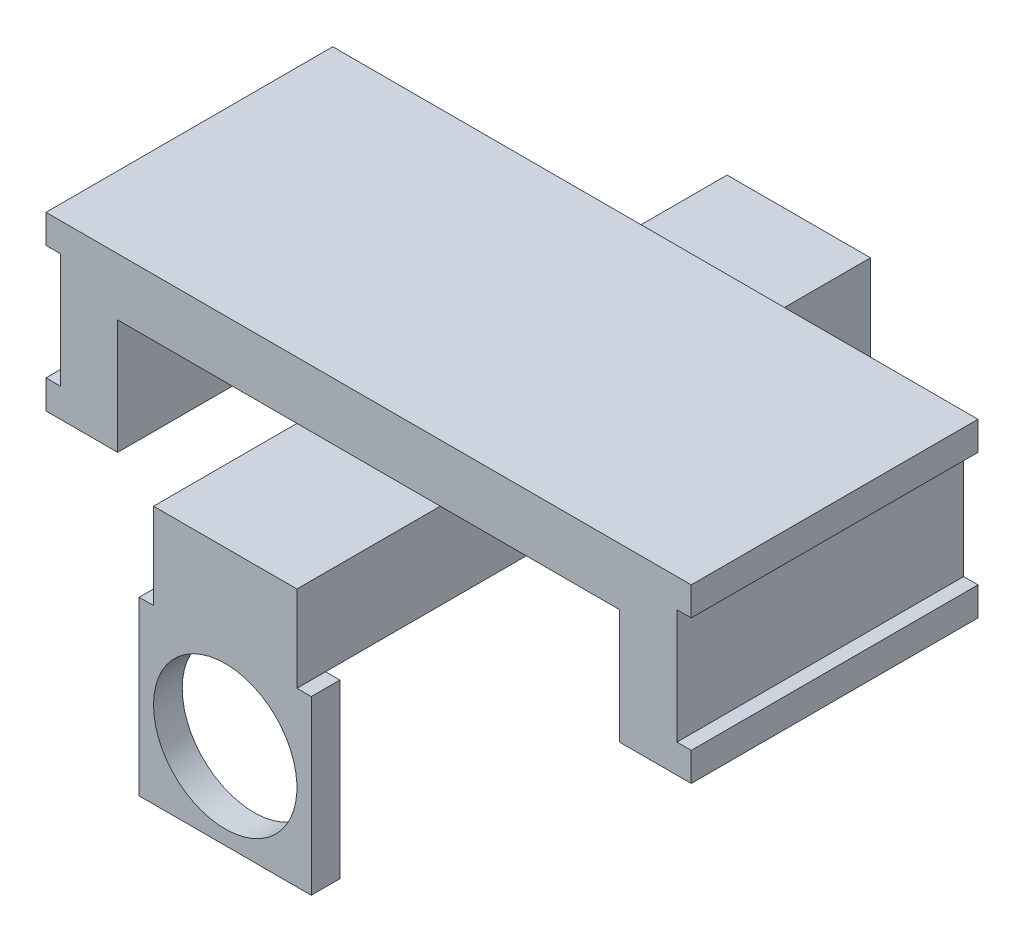
SolidWorks part; units mm, degrees
ref_plane "Front Plane" through (0, 0, 0) normal (0, 0, 1) x (1, 0, 0)
ref_plane "Top Plane" through (0, 0, 0) normal (0, 1, 0) x (1, 0, 0)
ref_plane "Right Plane" through (0, 0, 0) normal (1, 0, 0) x (0, 0, -1)
sketch "Sketch1" plane through (0, 0, 0) normal (0, 1, 0) x (1, 0, 0)
  line L1 (-28.575, -12.7) -> (28.575, -12.7)
  line L2 (-28.575, -12.7) -> (-28.575, 12.7)
  line L3 (-28.575, 12.7) -> (28.575, 12.7)
  line L4 (28.575, -12.7) -> (28.575, 12.7)
  line L5 (-28.575, -12.7) -> (28.575, 12.7) construction
  line L6 (-28.575, 12.7) -> (28.575, -12.7) construction
  point P0 (0, 0)
  dimension "D1" = 25.4
  dimension "D2" = 57.15
extrude "Boss-Extrude1" add sketch "Sketch1" along normal blind 15.24
sketch "Sketch2" plane through (0, 0, 0) normal (0, -1, 0) x (1, 0, 0)
  line L0 (-28.575, 12.7) -> (28.575, 12.7) construction
  line L1 (-22.225, 12.7) -> (22.225, 12.7)
  line L2 (-22.225, 12.7) -> (-22.225, -12.7)
  line L3 (-22.225, -12.7) -> (22.225, -12.7)
  line L4 (22.225, 12.7) -> (22.225, -12.7)
  line L5 (28.575, -12.7) -> (-28.575, -12.7) construction
  line L6 (0, 12.7) -> (0, 0) construction
  line L7 (-28.575, -12.7) -> (-28.575, 12.7) construction
  point P8 (0, 12.7)
  dimension "D1" = 6.35
extrude "Cut-Extrude1" cut sketch "Sketch2" against normal blind 10.16
sketch "Sketch3" plane through (0, 0, 12.7) normal (0, 0, 1) x (1, 0, 0)
  line L0 (-28.575, 15.24) -> (-28.575, 0) construction
  line L1 (-28.575, 12.7) -> (-27.305, 12.7)
  line L2 (-28.575, 12.7) -> (-28.575, 2.54)
  line L3 (-28.575, 2.54) -> (-27.305, 2.54)
  line L4 (-27.305, 12.7) -> (-27.305, 2.54)
  line L5 (28.575, 15.24) -> (28.575, 0) construction
  line L6 (28.575, 12.7) -> (27.305, 12.7)
  line L7 (28.575, 12.7) -> (28.575, 2.54)
  line L8 (28.575, 2.54) -> (27.305, 2.54)
  line L9 (27.305, 12.7) -> (27.305, 2.54)
  line L10 (22.225, 10.16) -> (-22.225, 10.16) construction
  dimension "D1" = 1.27
  dimension "D2" = 10.16
  dimension "D3" = 2.54
extrude "Cut-Extrude2" cut sketch "Sketch3" against normal through all
sketch "Sketch4" plane through (0, 0, 0) normal (0, -1, 0) x (1, 0, 0)
  line L1 (-6.35, -25.4) -> (6.35, -25.4)
  line L2 (-6.35, -25.4) -> (-6.35, 25.4)
  line L3 (-6.35, 25.4) -> (6.35, 25.4)
  line L4 (6.35, -25.4) -> (6.35, 25.4)
  point P4 (-12.7, 0)
  point P6 (0, 0)
  dimension "D1" = 6.35
  dimension "D2" = 50.8
  dimension "D3" = 12.7
  dimension "D4" = 25.4
extrude "Boss-Extrude2" add sketch "Sketch4" along normal blind 7.62 from surface at -10.16 starting at face at (0, 10.16, 0)
sketch "Sketch6" plane through (0, 0, -25.4) normal (0, 0, -1) x (-1, 0, 0)
  line L0 (-7.62, 2.54) -> (-7.62, -12.7)
  line L1 (6.35, 2.54) -> (-6.35, 2.54) construction
  line L2 (-7.62, -12.7) -> (7.62, -12.7)
  line L3 (7.62, -12.7) -> (7.62, 2.54)
  line L4 (7.62, 2.54) -> (-7.62, 2.54)
  line L5 (-7.62, 2.54) -> (7.62, -12.7) construction
  line L6 (6.35, 2.54) -> (-6.35, 2.54) construction
  circle A0 centre (0, -5.08) radius 6.35
  point P8 (0, -2.54)
  point P9 (0, 2.54)
  dimension "D1" = 12.7
  dimension "D2" = 15.24
  dimension "D3" = 15.24
extrude "Boss-Extrude3" add sketch "Sketch6" against normal blind 2.54
mirror "Mirror1" about plane through (0, 0, 0) normal (0, 0, 1) of "Boss-Extrude3"
